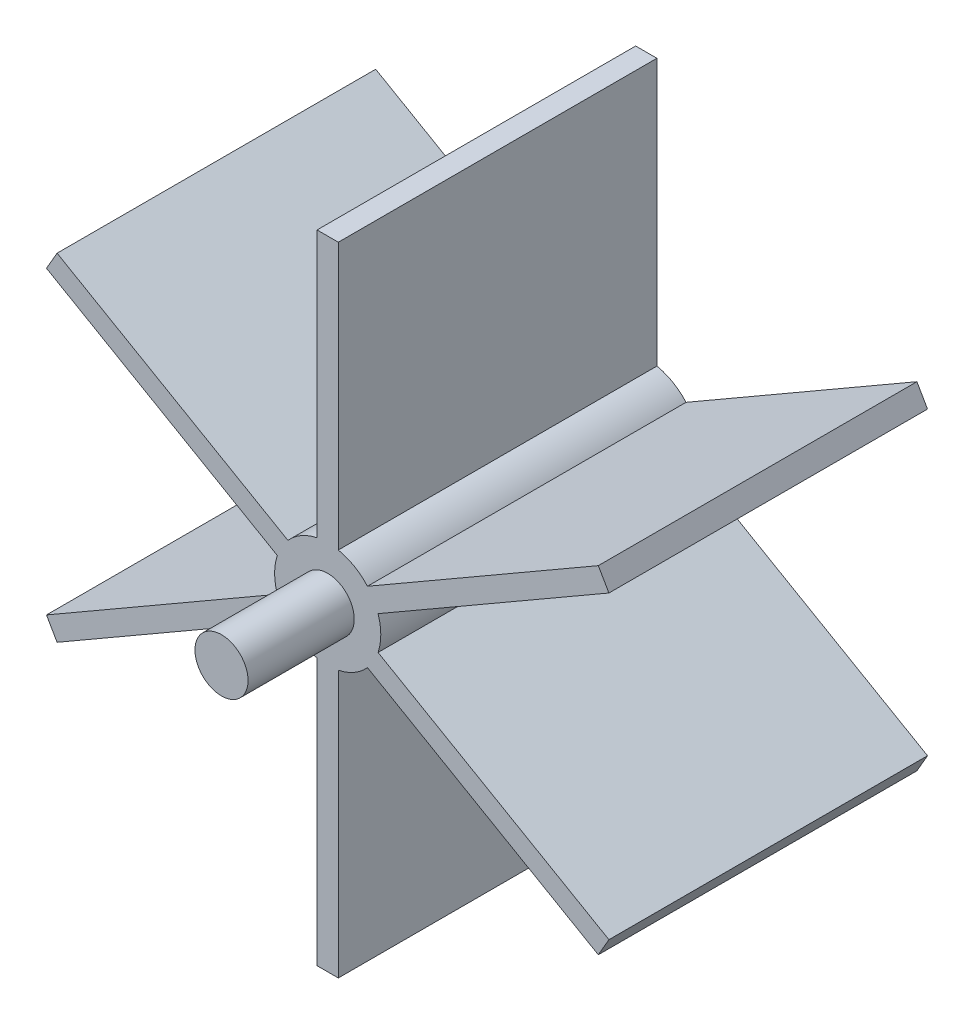
SolidWorks part; units mm, degrees
ref_plane "Front Plane" through (0, 0, 0) normal (0, 0, 1) x (1, 0, 0)
ref_plane "Top Plane" through (0, 0, 0) normal (0, 1, 0) x (1, 0, 0)
ref_plane "Right Plane" through (0, 0, 0) normal (1, 0, 0) x (0, 0, -1)
sketch "Sketch1" plane through (0, 0, 0) normal (0, 0, 1) x (1, 0, 0)
  line L0 (0, 0) -> (0, 76.2)
  line L1 (0, 0) -> (65.9911, 38.1)
  line L2 (0, 0) -> (65.9911, -38.1)
  line L3 (0, 0) -> (0, -76.2)
  line L4 (0, 0) -> (-65.9911, -38.1)
  line L5 (0, 0) -> (-65.9911, 38.1)
  line L6 (2.54, 0) -> (2.54, 76.2)
  line L7 (1.27, -2.1997) -> (67.2611, 35.9003)
  line L8 (-1.27, -2.1997) -> (64.7211, -40.2997)
  line L9 (-2.54, 0) -> (-2.54, 76.2)
  line L10 (-1.27, 2.1997) -> (64.7211, 40.2997)
  line L11 (1.27, 2.1997) -> (67.2611, -35.9003)
  line L12 (-2.54, 0) -> (-2.54, -76.2)
  line L13 (-1.27, 2.1997) -> (-67.2611, -35.9003)
  line L14 (1.27, 2.1997) -> (-64.7211, 40.2997)
  line L15 (2.54, 0) -> (2.54, -76.2)
  line L16 (1.27, -2.1997) -> (-64.7211, -40.2997)
  line L17 (-1.27, -2.1997) -> (-67.2611, 35.9003)
  line L18 (-67.2611, 35.9003) -> (-64.7211, 40.2997)
  line L19 (-2.54, 76.2) -> (2.54, 76.2)
  line L20 (64.7211, 40.2997) -> (67.2611, 35.9003)
  line L21 (64.7211, -40.2997) -> (67.2611, -35.9003)
  line L22 (2.54, -76.2) -> (-2.54, -76.2)
  line L23 (-64.7211, -40.2997) -> (-67.2611, -35.9003)
  circle A0 centre (0, 0) radius 12.7
  point P10 (0, 0)
  dimension "D7" = 25.4
  dimension "D1" = 76.2
  dimension "D3" = 2.54
  dimension "D4" = 2.54
  dimension "D5" = 2.54
  dimension "D6" = 2.54
  dimension "D2" = 6
extrude "Boss-Extrude1" add sketch "Sketch1" along normal blind 76.2 contours A0 L5 L18 L17 | A0 L14 L18 L5 | A0 L0 L19 L9 | A0 L6 L19 L0 | A0 L1 L20 L10 | A0 L7 L20 L1 | A0 L2 L21 L11 | A0 L8 L21 L2 | A0 L3 L22 L15 | A0 L12 L22 L3 | A0 L4 L23 L16 | A0 L13 L23 L4
sketch "Sketch2" plane through (0, 0, 76.2) normal (0, 0, 1) x (1, 0, 0)
  circle A0 centre (0, 0) radius 6.35
  dimension "D1" = 12.7
extrude "Boss-Extrude2" add sketch "Sketch2" along normal blind 25.4
